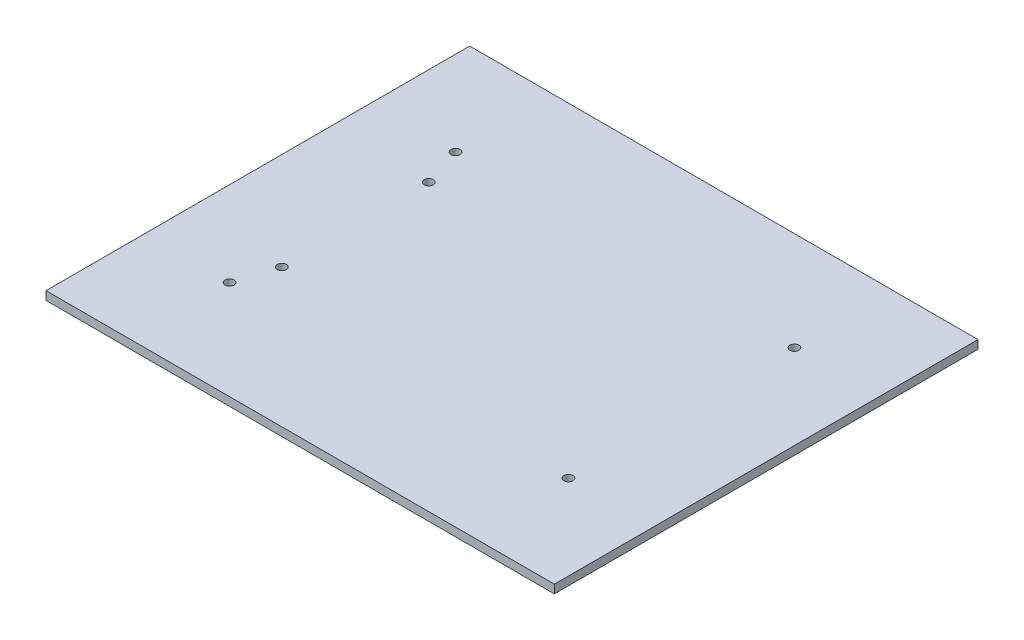
SolidWorks part; units mm, degrees
ref_plane "Front" through (0, 0, 0) normal (0, 0, 1) x (1, 0, 0)
ref_plane "Top" through (0, 0, 0) normal (0, 1, 0) x (1, 0, 0)
ref_plane "Right" through (0, 0, 0) normal (1, 0, 0) x (0, 0, -1)
sketch "Sketch1" plane through (0, 0, 0) normal (0, 1, 0) x (1, 0, 0)
  line L1 (-90, -75) -> (90, -75)
  line L2 (-90, -75) -> (-90, 75)
  line L3 (-90, 75) -> (90, 75)
  line L4 (90, -75) -> (90, 75)
  line L5 (-90, -75) -> (90, 75) construction
  line L6 (-90, 75) -> (90, -75) construction
  circle A0 centre (-60, -40) radius 1.6
  circle A1 centre (-60, 40) radius 1.6
  circle A2 centre (60, -40) radius 1.6
  circle A3 centre (60, 40) radius 1.6
  circle A4 centre (-55.5, -26) radius 1.6
  circle A5 centre (-55.5, 26) radius 1.6
  dimension "D3" = 3.2
  dimension "D5" = 3.2
  dimension "D1" = 180
  dimension "D2" = 150
  dimension "D4" = 30
  dimension "D8" = 55.5
  dimension "D9" = 26
  dimension "D10" = 2
  dimension "D6" = 2
  dimension "D7" = 2
extrude "Boss-Extrude1" add sketch "Sketch1" along normal blind 3
